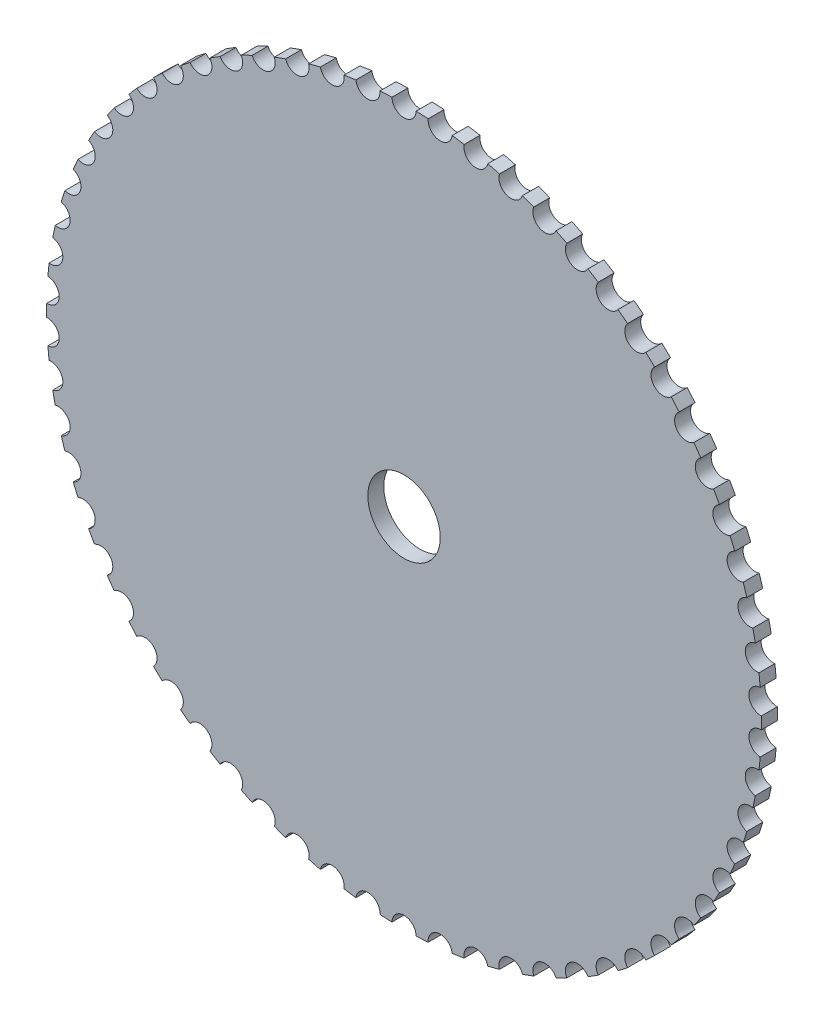
SolidWorks part; units mm, degrees
material "Plain Carbon Steel"
ref_plane "Front Plane" through (0, 0, 0) normal (0, 0, 1) x (1, 0, 0)
ref_plane "Top Plane" through (0, 0, 0) normal (0, 1, 0) x (1, 0, 0)
ref_plane "Right Plane" through (0, 0, 0) normal (1, 0, 0) x (0, 0, -1)
sketch "Sketch1" plane through (0, 0, 0) normal (0, 0, 1) x (1, 0, 0)
  line L0 (0, 0) -> (0, 93.98) construction
  circle A0 centre (0, 0) radius 9.525
  circle A1 centre (0, 0) radius 93.98
  dimension "D1" = 19.05
  dimension "D2" = 187.96
extrude "Extrude1" add sketch "Sketch1" along normal mid plane 4.191
sketch "Sketch2" plane through (0, 0, -2.0955) normal (0, 0, -1) x (-1, 0, 0)
  line L0 (0, 0) -> (0, 90.805) construction
  arc A0 (-3.1745, 93.9264) -> (3.1745, 93.9264) centre (0, 93.98) ccw
  circle A1 centre (0, 0) radius 93.98 construction
  arc A2 (3.1745, 93.9264) -> (-3.1745, 93.9264) centre (0, 0) ccw
  dimension "D1" = 3.175
  dimension "D2" = 90.805
extrude "Extrude2" cut sketch "Sketch2" against normal up to next
pattern_circular "CirPattern1" count 62 over 360 about axis through (0, 0, 0) along (0, 0, 1) of "Extrude2"
